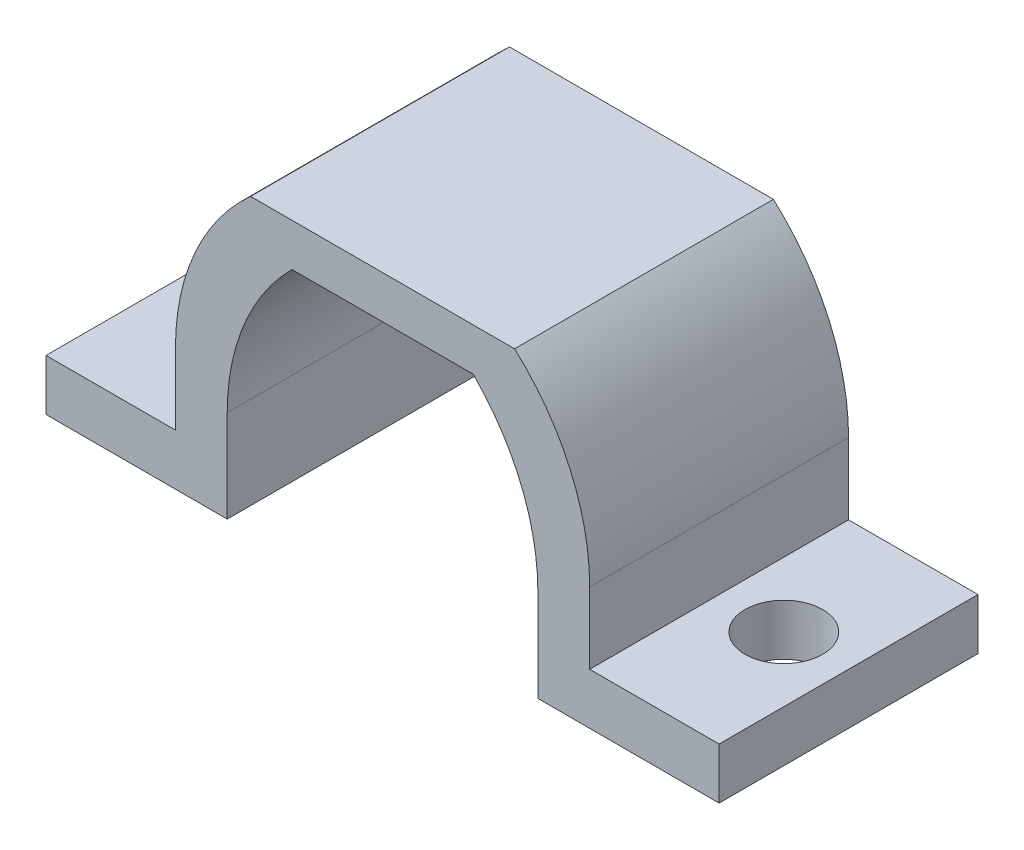
SolidWorks part; units mm, degrees
material "PLA"
ref_plane "Plano frontal" through (0, 0, 0) normal (0, 0, 1) x (1, 0, 0)
ref_plane "Plano superior" through (0, 0, 0) normal (0, 1, 0) x (1, 0, 0)
ref_plane "Plano direito" through (0, 0, 0) normal (1, 0, 0) x (0, 0, -1)
sketch "Esboço2" plane through (0, 0, 0) normal (0, 0, 1) x (1, 0, 0)
  line L14 (-2.1627, 4.1308) -> (4.8373, 4.1308)
  line L16 (-7.4967, -0.3871) -> (11.4156, -0.3871) construction
  line L17 (-3.7616, 5.7774) -> (6.4362, 5.7774)
  line L25 (9.3373, -0.74) -> (9.3373, -3.4932)
  line L28 (14.3373, -3.4932) -> (14.3373, -5.4692)
  line L29 (9.3373, -3.4932) -> (14.3373, -3.4932)
  line L31 (7.3373, -5.4692) -> (14.3373, -5.4692)
  line L34 (7.3373, -5.4692) -> (7.3373, -1.9076)
  line L36 (1.3373, -5.4692) -> (7.3373, -5.4692) construction
  line L37 (1.3373, -7.2509) -> (1.3373, 8.6895) construction
  line L39 (-6.6627, -0.74) -> (-6.6627, -3.4932)
  line L40 (-6.6627, -3.4932) -> (-11.6627, -3.4932)
  line L41 (-11.6627, -3.4932) -> (-11.6627, -5.4692)
  line L42 (-4.6627, -5.4692) -> (-11.6627, -5.4692)
  line L43 (-4.6627, -5.4692) -> (-4.6627, -1.9076)
  arc A5 (7.3373, -1.9076) -> (4.8373, 4.1308) centre (-1.2051, -1.9076) ccw
  arc A7 (9.3373, -0.74) -> (6.4362, 5.7774) centre (0.5659, -0.74) ccw
  arc A8 (-6.6627, -0.74) -> (-3.7616, 5.7774) centre (2.1086, -0.74) cw
  arc A9 (-4.6627, -1.9076) -> (-2.1627, 4.1308) centre (3.8797, -1.9076) cw
  dimension "D6" = 9.6
  dimension "D2" = 5
  dimension "D5" = 7
extrude "Ressalto-extrusão1" add sketch "Esboço2" along normal blind 10
sketch "Esboço3" plane through (0, -3.4932, 0) normal (0, 1, 0) x (1, 0, 0)
  line L0 (-11.6627, -10) -> (-11.6627, 0) construction
  line L1 (-6.6627, 0) -> (-11.6627, 0) construction
  line L2 (1.3373, 0) -> (1.3373, -13.6996) construction
  line L3 (6.4362, 0) -> (-3.7616, 0) construction
  circle A0 centre (-9.1627, -5) radius 1.5
  circle A1 centre (11.8373, -5) radius 1.5
  dimension "D1" = 2.5
  dimension "D2" = 5
extrude "Corte-extrusão1" cut sketch "Esboço3" against normal blind 10
